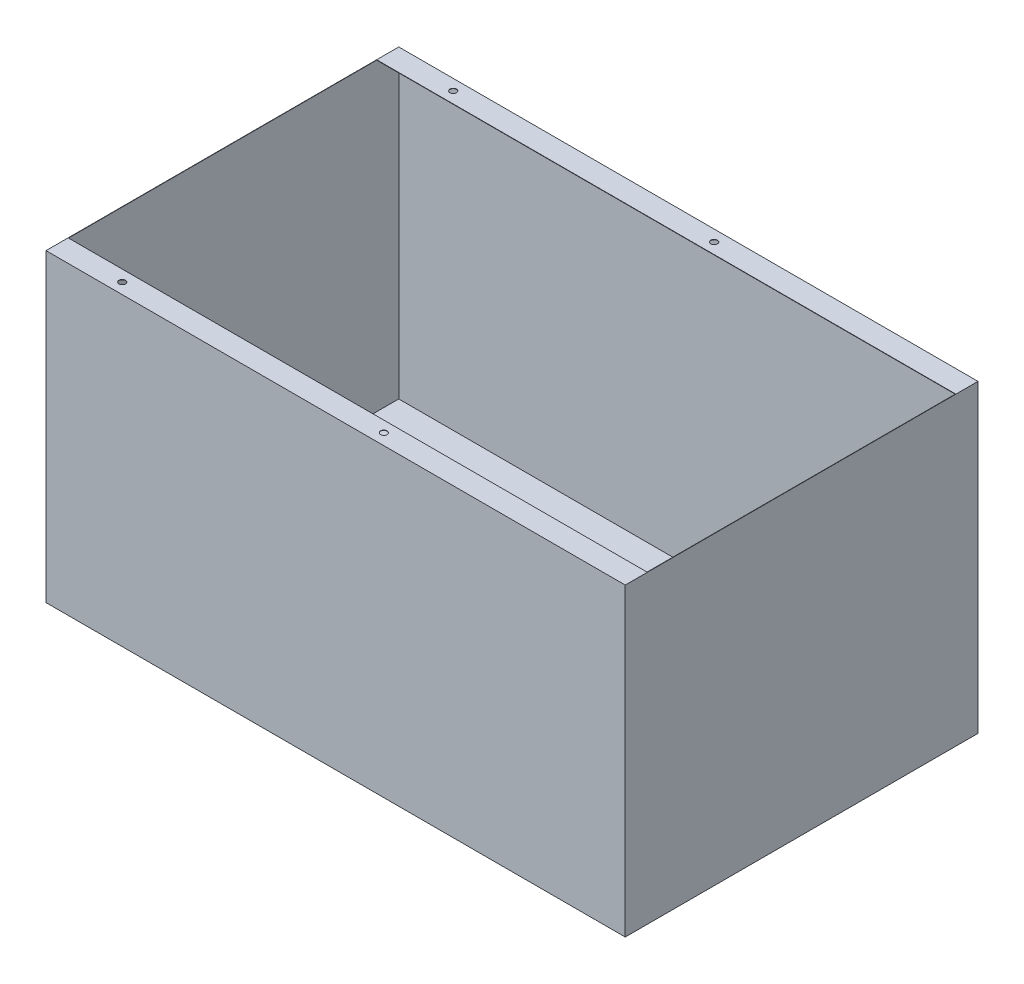
SolidWorks part; units mm, degrees
ref_plane "Front Plane" through (0, 0, 0) normal (0, 0, 1) x (1, 0, 0)
ref_plane "Top Plane" through (0, 0, 0) normal (0, 1, 0) x (1, 0, 0)
ref_plane "Right Plane" through (0, 0, 0) normal (1, 0, 0) x (0, 0, -1)
sketch "Sketch1" plane through (0, 0, 0) normal (1, 0, 0) x (0, 0, -1)
  line L1 (0, 0) -> (2057.4, 0)
  line L2 (0, 0) -> (0, 1778)
  line L3 (0, 1778) -> (2057.4, 1778)
  line L4 (2057.4, 0) -> (2057.4, 1778)
  dimension "D1" = 2057.4
  dimension "D2" = 1778
extrude "Boss-Extrude1" add sketch "Sketch1" against normal blind 3378.2
sketch "Sketch2" plane through (0, 1778, 0) normal (0, 1, 0) x (1, 0, 0)
  line L0 (-3378.2, 2057.4) -> (0, 2057.4) construction
  line L1 (-2, 2) -> (-3376.2, 2)
  line L2 (-2, 2) -> (-2, 2055.4)
  line L3 (-2, 2055.4) -> (-3376.2, 2055.4)
  line L4 (-3376.2, 2) -> (-3376.2, 2055.4)
  line L5 (-2, 2) -> (-3376.2, 2055.4) construction
  line L6 (-2, 2055.4) -> (-3376.2, 2) construction
  line L7 (0, 2057.4) -> (0, 0) construction
  line L8 (-3378.2, 0) -> (0, 0) construction
  line L9 (-3378.2, 2057.4) -> (-3378.2, 0) construction
  point P0 (-1689.1, 1028.7)
  dimension "D1" = 2
  dimension "D2" = 2
  dimension "D3" = 2
  dimension "D4" = 2
extrude "Cut-Extrude1" cut sketch "Sketch2" against normal blind 1776
sketch "Sketch3" plane through (0, 0, -2055.4) normal (0, 0, 1) x (1, 0, 0)
  line L1 (-3376.2, 1778) -> (-2, 1778)
  line L2 (-3376.2, 1778) -> (-3376.2, 1776)
  line L3 (-3376.2, 1776) -> (-2, 1776)
  line L4 (-2, 1778) -> (-2, 1776)
  dimension "D1" = 2
extrude "Boss-Extrude2" add sketch "Sketch3" along normal blind 127
sketch "Sketch4" plane through (0, 0, -2) normal (0, 0, -1) x (-1, 0, 0)
  line L1 (2, 1778) -> (3376.2, 1778)
  line L2 (2, 1778) -> (2, 1776)
  line L3 (2, 1776) -> (3376.2, 1776)
  line L4 (3376.2, 1778) -> (3376.2, 1776)
  dimension "D1" = 2
extrude "Boss-Extrude3" add sketch "Sketch4" along normal blind 127
sketch "Sketch5" plane through (0, 1778, 0) normal (0, 1, 0) x (1, 0, 0)
  line L0 (0, 2057.4) -> (0, 0) construction
  line L1 (-3376.2, 129) -> (-2, 129) construction
  line L2 (-2, 1928.4) -> (-3376.2, 1928.4) construction
  line L3 (-3378.2, 0) -> (0, 0) construction
  line L4 (-3378.2, 2057.4) -> (0, 2057.4) construction
  circle A0 centre (-1473.2, 65.5) radius 19.05
  circle A1 centre (-1473.2, 1991.9) radius 19.05
  circle A2 centre (-2997.2, 1993.9) radius 19.05
  circle A3 centre (-2997.2, 63.5) radius 19.05
  dimension "D1" = 38.1
  dimension "D2" = 38.1
  dimension "D3" = 1473.2
  dimension "D4" = 63.5
  dimension "D5" = 1473.2
  dimension "D6" = 63.5
  dimension "D7" = 38.1
  dimension "D8" = 38.1
  dimension "D9" = 63.5
  dimension "D10" = 63.5
  dimension "D11" = 1524
  dimension "D12" = 1524
extrude "Cut-Extrude2" cut sketch "Sketch5" against normal up to next
scale "Scale1" scale about centroid uniform scaling yes scale factor 2.54
